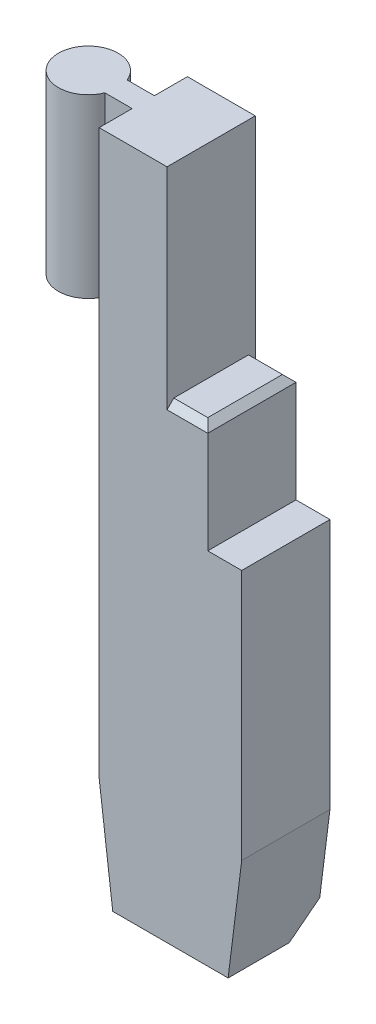
SolidWorks part; units mm, degrees
ref_plane "Płaszczyzna przednia" through (0, 0, 0) normal (0, 0, 1) x (1, 0, 0)
ref_plane "Płaszczyzna górna" through (0, 0, 0) normal (0, 1, 0) x (1, 0, 0)
ref_plane "Płaszczyzna prawa" through (0, 0, 0) normal (1, 0, 0) x (0, 0, -1)
sketch "Szkic1" plane through (0, 0, 0) normal (0, 0, 1) x (1, 0, 0)
  line L1 (-5.25, 20) -> (5.25, 20)
  line L2 (-5.25, 20) -> (-5.25, -20)
  line L3 (-5.25, -20) -> (5.25, -20)
  line L4 (5.25, 20) -> (5.25, -20)
  line L5 (-5.25, 20) -> (5.25, -20) construction
  line L6 (-5.25, -20) -> (5.25, 20) construction
  point P0 (0, 0)
  dimension "D1" = 10.5
  dimension "D2" = 40
extrude "Dodanie-wyciągnięcie1" add sketch "Szkic1" along normal blind 6.5
sketch "Szkic2" plane through (0, 0, 6.5) normal (0, 0, 1) x (1, 0, 0)
  line L0 (-0.25, 20) -> (-0.25, 5)
  line L1 (5.25, 20) -> (-5.25, 20) construction
  line L2 (-0.25, 5) -> (5.25, 5)
  line L3 (5.25, -20) -> (5.25, 20) construction
  line L4 (5.25, 5) -> (5.25, 20)
  line L5 (5.25, 20) -> (-0.25, 20)
  line L6 (-5.25, 20) -> (-5.25, -20) construction
  line L8 (2.75, 5) -> (5.25, 5)
  line L9 (2.75, 5) -> (2.75, -3)
  line L10 (2.75, -3) -> (5.25, -3)
  line L11 (5.25, 5) -> (5.25, -3)
  line M6 (5.25, -20) -> (5.25, 20)
  line M7 (5.25, 20) -> (-5.25, 20)
  dimension "5" = 5
  dimension "D2" = 15
  dimension "D3" = 8
  dimension "D4" = 8
extrude "Wytnij-wyciągnięcie1" cut sketch "Szkic2" against normal blind 6.5 contours L9 L10 L2 M6 | L0 L2 M6 M7
chamfer "Sfazowanie1" distance 0.5 angle 45 3 edges at (1.25, 5, 0) (2.75, 5, 3.25) (1.25, 5, 6.5)
sketch "Szkic3" plane through (0, 20, 0) normal (0, 1, 0) x (1, 0, 0)
  line L0 (-5.25, -3.25) -> (-9.3, -3.25) construction
  line L1 (-5.25, -6.5) -> (-5.25, 0) construction
  line L3 (-5.25, -4.0704) -> (-9.3, -4.0704)
  line L4 (-5.25, -4.0704) -> (-5.25, -2.4296)
  line L5 (-5.25, -2.4296) -> (-9.3, -2.4296)
  line L6 (-9.3, -4.0704) -> (-9.3, -2.4296)
  line L7 (-5.25, -4.0704) -> (-9.3, -2.4296) construction
  line L8 (-5.25, -2.4296) -> (-9.3, -4.0704) construction
  circle A0 centre (-9.3, -3.25) radius 2.2
  point P5 (-7.275, -3.25)
  line M10 (-5.25, 0) -> (-5.25, -6.5)
  dimension "D2" = 4.4
  dimension "D1" = 4.05
extrude "Dodanie-wyciągnięcie2" add sketch "Szkic3" against normal blind 13 contours L5 A0 L3 L6 | L3 A0 L5 L6 | A0 L3 L5 M10
sketch "Szkic4" plane through (0, 0, 6.5) normal (0, 0, 1) x (1, 0, 0)
  line L0 (-5.25, -20) -> (5.25, -20) construction
  line L1 (-5.25, -20) -> (5.25, -20)
  line L2 (-5.25, -20) -> (-5.25, -29.5)
  line L3 (-5.25, -29.5) -> (5.25, -29.5)
  line L4 (5.25, -20) -> (5.25, -29.5)
  line L5 (5.25, -20) -> (5.25, -3) construction
  line L7 (5.75, -36.5) -> (-5.75, -36.5)
  point P6 (5.25, -20)
  point P11 (-5.25, -20)
  point P12 (-5.25, -20)
  line M11 (-5.25, -20) -> (5.25, -20)
  dimension "D1" = 7
extrude "Dodanie-wyciągnięcie3" add sketch "Szkic4" against normal up to vertex (6.5 mm away) contours L4 L2 L3 M11 up to point (-5.25, -20, 0)
chamfer "Sfazowanie2" distance 8 distance2 1 1 edges at (5.25, -29.5, 3.25)
chamfer "Sfazowanie3" distance 1 distance2 8 1 edges at (-5.25, -29.5, 3.25)
chamfer "Sfazowanie4" distance 2 angle 45 1 edges at (0, -29.5, 0)
